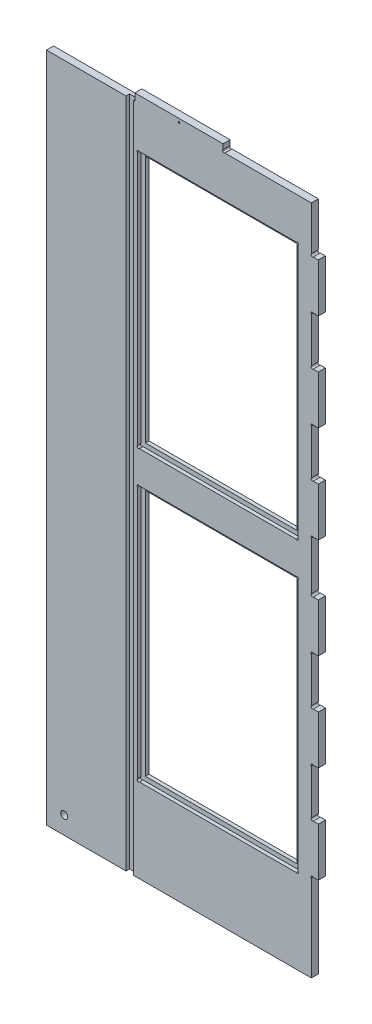
SolidWorks part; units mm, degrees
ref_plane "Plan de face" through (0, 0, 0) normal (0, 0, 1) x (1, 0, 0)
ref_plane "Plan de dessus" through (0, 0, 0) normal (0, 1, 0) x (1, 0, 0)
ref_plane "Plan de droite" through (0, 0, 0) normal (1, 0, 0) x (0, 0, -1)
sketch "Esquisse1" plane through (0, 0, 0) normal (0, 0, 1) x (1, 0, 0)
  line L0 (-54.6501, -45.8192) -> (-54.6501, 358.029)
  line L1 (45.3499, 722.8961) -> (145.3499, 722.8961)
  line L2 (-54.6501, -45.8192) -> (-46.6501, -45.8192) construction
  line L3 (245.3499, 714.8961) -> (245.3499, 665.0174)
  line L4 (245.3499, -45.8192) -> (-54.6501, -45.8192)
  line L5 (-54.6501, 358.029) -> (245.3499, 358.029) construction
  line L6 (-54.6501, 358.029) -> (-237.0836, 540.4625) construction
  line L7 (-237.0836, 540.4625) -> (-54.6501, 722.8961) construction
  line L8 (-54.6501, 358.029) -> (-54.6501, 714.8961)
  line L9 (53.3499, 662.8961) -> (225.3499, 662.8961)
  line L10 (53.3499, 662.8961) -> (53.3499, 381.3427)
  line L11 (-46.6501, -45.8192) -> (-46.6501, 354.7153) construction
  line L12 (53.3499, 381.3427) -> (225.3499, 381.3427)
  line L13 (-46.6501, 354.7153) -> (203.3499, 604.7153) construction
  line L14 (225.3499, 662.8961) -> (225.3499, 381.3427)
  line L15 (53.3499, 334.7153) -> (225.3499, 334.7153)
  line L16 (53.3499, 334.7153) -> (53.3499, 54.1808)
  line L17 (53.3499, 54.1808) -> (225.3499, 54.1808)
  line L18 (225.3499, 334.7153) -> (225.3499, 54.1808)
  line L19 (-54.6501, 354.7153) -> (245.3499, 354.7153) construction
  line L20 (-54.6501, 358.029) -> (-46.6501, 354.7153) construction
  line L21 (-54.6501, 358.029) -> (-46.6501, 361.3427) construction
  line L22 (-46.6501, 354.7153) -> (-46.6501, 361.3427) construction
  line L23 (-54.6501, 361.3427) -> (245.3499, 361.3427) construction
  line L24 (-54.6501, 662.8961) -> (245.3499, 662.8961) construction
  line L25 (-54.6501, 607.8961) -> (245.3499, 607.8961) construction
  line L26 (-54.6501, 552.8961) -> (245.3499, 552.8961) construction
  line L27 (-54.6501, 497.8961) -> (245.3499, 497.8961) construction
  line L28 (-54.6501, 442.8961) -> (245.3499, 442.8961) construction
  line L29 (-54.6501, 387.8961) -> (245.3499, 387.8961) construction
  line L30 (-54.6501, 54.1808) -> (245.3499, 54.1808) construction
  line L31 (-54.6501, 109.1808) -> (245.3499, 109.1808) construction
  line L32 (-54.6501, 164.1808) -> (245.3499, 164.1808) construction
  line L33 (-54.6501, 219.1808) -> (245.3499, 219.1808) construction
  line L34 (-54.6501, 274.1808) -> (245.3499, 274.1808) construction
  line L35 (-54.6501, 329.1808) -> (245.3499, 329.1808) construction
  line L36 (245.3499, 722.8961) -> (253.3499, 722.8961) construction
  line L37 (253.3499, 722.8961) -> (253.3499, -45.8192) construction
  line L38 (253.3499, -45.8192) -> (245.3499, -45.8192) construction
  line L39 (247.4712, 662.8961) -> (253.3499, 662.8961)
  line L40 (253.3499, 662.8961) -> (253.3499, 607.8961)
  line L41 (253.3499, 607.8961) -> (247.4712, 607.8961)
  line L42 (247.4712, 552.8961) -> (253.3499, 552.8961)
  line L43 (253.3499, 552.8961) -> (253.3499, 497.8961)
  line L44 (253.3499, 497.8961) -> (247.4712, 497.8961)
  line L45 (247.4712, 442.8961) -> (253.3499, 442.8961)
  line L46 (253.3499, 442.8961) -> (253.3499, 387.8961)
  line L47 (253.3499, 387.8961) -> (247.4712, 387.8961)
  line L48 (247.4712, 54.1808) -> (253.3499, 54.1808)
  line L49 (253.3499, 54.1808) -> (253.3499, 109.1808)
  line L50 (253.3499, 109.1808) -> (247.4712, 109.1808)
  line L51 (247.4712, 164.1808) -> (253.3499, 164.1808)
  line L52 (253.3499, 164.1808) -> (253.3499, 219.1808)
  line L53 (253.3499, 219.1808) -> (247.4712, 219.1808)
  line L54 (247.4712, 274.1808) -> (253.3499, 274.1808)
  line L55 (253.3499, 274.1808) -> (253.3499, 329.1808)
  line L56 (253.3499, 329.1808) -> (247.4712, 329.1808)
  line L57 (245.3499, 52.0595) -> (245.3499, -45.8192)
  line L58 (245.3499, 162.0595) -> (245.3499, 111.3021)
  line L59 (245.3499, 272.0595) -> (245.3499, 221.3021)
  line L60 (245.3499, 385.7748) -> (245.3499, 331.3021)
  line L61 (245.3499, 495.7748) -> (245.3499, 445.0174)
  line L62 (245.3499, 605.7748) -> (245.3499, 555.0174)
  line L63 (-54.6501, 749.0762) -> (45.3499, 749.0762) construction
  line L64 (45.3499, 749.0762) -> (145.3499, 749.0762) construction
  line L65 (145.3499, 749.0762) -> (245.3499, 749.0762) construction
  line L66 (45.3499, 722.8961) -> (45.3499, 717.0174)
  line L67 (43.2286, 714.8961) -> (-54.6501, 714.8961)
  line L68 (145.3499, 722.8961) -> (145.3499, 717.0174)
  line L69 (147.4712, 714.8961) -> (245.3499, 714.8961)
  line L70 (45.3499, 741.0121) -> (45.3499, 675.6882) construction
  line L71 (95.3499, 762.5448) -> (95.3499, 710.2857) construction
  line L72 (110.1282, 718.8961) -> (91.2569, 718.8961) construction
  arc A0 (145.3499, 717.0174) -> (147.4712, 714.8961) centre (146.4106, 715.9567) ccw
  arc A1 (43.2286, 714.8961) -> (45.3499, 717.0174) centre (44.2892, 715.9567) ccw
  arc A2 (245.3499, 665.0174) -> (247.4712, 662.8961) centre (246.4106, 663.9567) ccw
  arc A3 (247.4712, 607.8961) -> (245.3499, 605.7748) centre (246.4106, 606.8354) ccw
  arc A4 (245.3499, 555.0174) -> (247.4712, 552.8961) centre (246.4106, 553.9567) ccw
  arc A5 (245.3499, 445.0174) -> (247.4712, 442.8961) centre (246.4106, 443.9567) ccw
  arc A6 (247.4712, 497.8961) -> (245.3499, 495.7748) centre (246.4106, 496.8354) ccw
  arc A7 (247.4712, 387.8961) -> (245.3499, 385.7748) centre (246.4106, 386.8354) ccw
  arc A8 (245.3499, 331.3021) -> (247.4712, 329.1808) centre (246.4106, 330.2415) ccw
  arc A9 (247.4712, 274.1808) -> (245.3499, 272.0595) centre (246.4106, 273.1201) ccw
  arc A10 (245.3499, 221.3021) -> (247.4712, 219.1808) centre (246.4106, 220.2415) ccw
  arc A11 (247.4712, 164.1808) -> (245.3499, 162.0595) centre (246.4106, 163.1201) ccw
  arc A12 (245.3499, 111.3021) -> (247.4712, 109.1808) centre (246.4106, 110.2415) ccw
  arc A13 (247.4712, 54.1808) -> (245.3499, 52.0595) centre (246.4106, 53.1201) ccw
  circle A14 centre (95.3499, 718.8961) radius 1
  dimension "D24" = 8
  dimension "D26" = 50
  dimension "D1" = 100
  dimension "D2" = 108
  dimension "D3" = 403.8482
  dimension "D4" = 108
  dimension "D5" = 20
  dimension "D6" = 8
  dimension "D7" = 20
  dimension "D8" = 300
  dimension "D9" = 22.5
  dimension "D10" = 20
  dimension "D11" = 20
  dimension "D12" = 60
  dimension "D13" = 60
  dimension "D14" = 55
  dimension "D15" = 55
  dimension "D16" = 55
  dimension "D17" = 55
  dimension "D18" = 55
  dimension "D19" = 55
  dimension "D20" = 55
  dimension "D21" = 55
  dimension "D22" = 55
  dimension "D23" = 55
  dimension "D25" = 8
  dimension "D27" = 4
extrude "Boss.-Extru.1" add sketch "Esquisse1" along normal blind 8
sketch "Esquisse2" plane through (0, 0, 8) normal (0, 0, 1) x (1, 0, 0)
  line L0 (225.3499, 334.7153) -> (53.3499, 334.7153) construction
  line L1 (50.4712, 339.7153) -> (228.2286, 339.7153)
  line L2 (48.3499, 337.5939) -> (48.3499, 51.3021)
  line L3 (50.4712, 49.1808) -> (228.2286, 49.1808)
  line L4 (230.3499, 337.5939) -> (230.3499, 51.3021)
  line L5 (53.3499, 334.7153) -> (53.3499, 54.1808) construction
  line L6 (225.3499, 54.1808) -> (225.3499, 334.7153) construction
  line L7 (53.3499, 54.1808) -> (225.3499, 54.1808) construction
  line L8 (225.3499, 662.8961) -> (53.3499, 662.8961) construction
  line L9 (50.4712, 667.8961) -> (228.2286, 667.8961)
  line L10 (48.3499, 665.7748) -> (48.3499, 378.464)
  line L11 (50.4712, 376.3427) -> (228.2286, 376.3427)
  line L12 (230.3499, 665.7748) -> (230.3499, 378.464)
  line L13 (53.3499, 662.8961) -> (53.3499, 381.3427) construction
  line L14 (225.3499, 381.3427) -> (225.3499, 662.8961) construction
  line L15 (53.3499, 381.3427) -> (225.3499, 381.3427) construction
  arc A0 (50.4712, 667.8961) -> (48.3499, 665.7748) centre (49.4106, 666.8354) ccw
  arc A1 (230.3499, 337.5939) -> (228.2286, 339.7153) centre (229.2892, 338.6546) ccw
  arc A2 (228.2286, 49.1808) -> (230.3499, 51.3021) centre (229.2892, 50.2415) ccw
  arc A3 (48.3499, 378.464) -> (50.4712, 376.3427) centre (49.4106, 377.4033) ccw
  arc A4 (50.4712, 339.7153) -> (48.3499, 337.5939) centre (49.4106, 338.6546) ccw
  arc A5 (230.3499, 665.7748) -> (228.2286, 667.8961) centre (229.2892, 666.8354) ccw
  arc A6 (228.2286, 376.3427) -> (230.3499, 378.464) centre (229.2892, 377.4033) ccw
  arc A7 (48.3499, 51.3021) -> (50.4712, 49.1808) centre (49.4106, 50.2415) ccw
  dimension "D5" = 5
  dimension "D1" = 5
  dimension "D2" = 5
  dimension "D3" = 5
  dimension "D4" = 5
  dimension "D6" = 5
  dimension "D7" = 5
  dimension "D8" = 5
extrude "Enlèv. mat.-Extru.1" cut sketch "Esquisse2" against normal blind 4
sketch "Esquisse3" plane through (0, 0, 8) normal (0, 0, 1) x (1, 0, 0)
  line L0 (35.3499, 714.8961) -> (35.3499, -45.8192) construction
  line L1 (43.2286, 714.8961) -> (-54.6501, 714.8961) construction
  line L2 (-54.6501, -45.8192) -> (245.3499, -45.8192) construction
  line L3 (-54.6501, 714.8961) -> (-54.6501, -45.8192) construction
  line L4 (35.3499, 714.8961) -> (43.8499, 714.8961) construction
  line L5 (43.8499, 714.8961) -> (43.8499, -45.8192) construction
  line L6 (43.8499, -45.8192) -> (35.3499, -45.8192) construction
  line L8 (35.3499, 714.8961) -> (43.8499, 714.8961)
  line L9 (35.3499, 714.8961) -> (35.3499, -45.8192)
  line L10 (35.3499, -45.8192) -> (43.8499, -45.8192)
  line L11 (43.8499, 714.8961) -> (43.8499, -45.8192)
  dimension "D1" = 90
extrude "Enlèv. mat.-Extru.2" cut sketch "Esquisse3" against normal blind 4
sketch "Esquisse4" plane through (0, 0, 8) normal (0, 0, 1) x (1, 0, 0)
  line L0 (-34.6501, -45.8192) -> (-34.6501, -25.8192) construction
  line L1 (-54.6501, -45.8192) -> (35.3499, -45.8192) construction
  line L2 (-54.6501, 714.8961) -> (-54.6501, -45.8192) construction
  circle A0 centre (-34.6501, -25.8192) radius 4
  dimension "D1" = 20
extrude "Enlèv. mat.-Extru.3" cut sketch "Esquisse4" against normal blind 6
sketch "Esquisse5" plane through (0, 0, 0) normal (0, 0, 1) x (1, 0, 0)
  line L0 (264.4326, 358.0327) -> (-65.4385, 358.0327)
